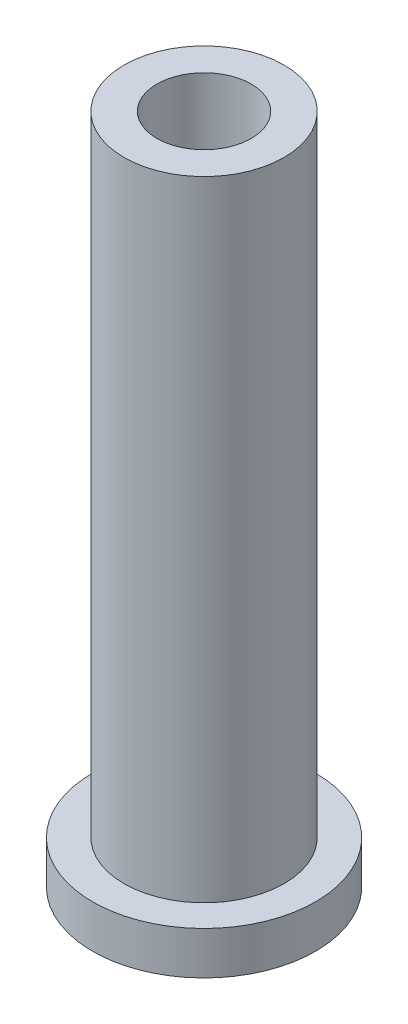
SolidWorks part; units mm, degrees
ref_plane "Front Plane" through (0, 0, 0) normal (0, 0, 1) x (1, 0, 0)
ref_plane "Top Plane" through (0, 0, 0) normal (0, 1, 0) x (1, 0, 0)
ref_plane "Right Plane" through (0, 0, 0) normal (1, 0, 0) x (0, 0, -1)
sketch "Reconstructed nominal axial profile" plane through (0, 0, 0) normal (0, 0, 1) x (1, 0, 0)
  line L0 (0, -500) -> (0, 50) construction
  line L1 (1.65, -1.5) -> (1.65, 22)
  line L2 (1.65, 22) -> (2.8, 22)
  line L3 (2.8, 22) -> (2.8, 0)
  line L4 (2.8, 0) -> (3.9, 0)
  line L5 (3.9, 0) -> (3.9, -1.5)
  line L6 (3.9, -1.5) -> (1.65, -1.5)
revolve "Native revolved geometry" add sketch "Reconstructed nominal axial profile" angle 360 about L0
